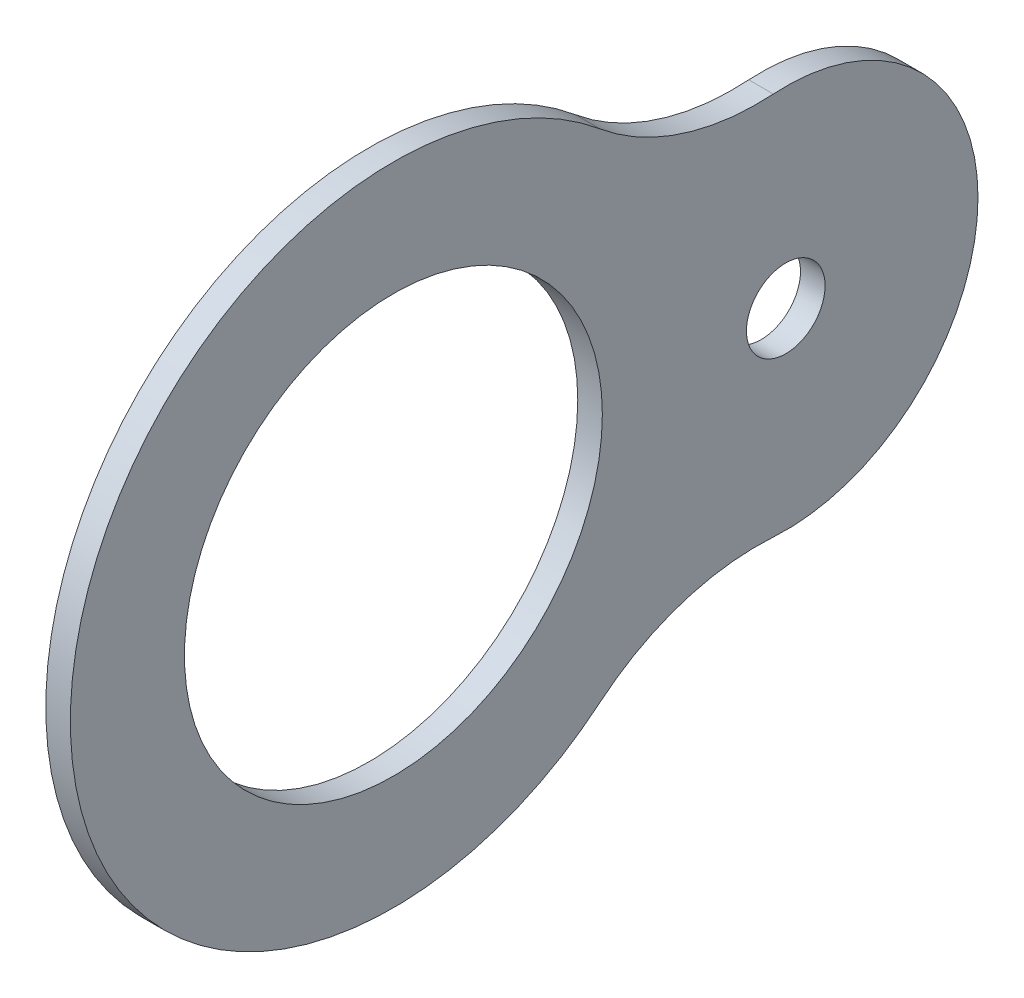
SolidWorks part; units mm, degrees
material "ABS"
ref_plane "Спереди" through (0, 0, 0) normal (0, 0, 1) x (1, 0, 0)
ref_plane "Сверху" through (0, 0, 0) normal (0, 1, 0) x (1, 0, 0)
ref_plane "Справа" through (0, 0, 0) normal (1, 0, 0) x (0, 0, -1)
sketch "Эскиз1" plane through (0, 0, 0) normal (1, 0, 0) x (0, 0, -1)
  circle A0 centre (27.5751, 7.5072) radius 1.5
  circle A1 centre (27.5751, 7.5072) radius 18.465
  circle A2 centre (14.9975, 25.9822) radius 7.885
  circle A3 centre (14.9975, 25.9822) radius 1.5
  circle A4 centre (0, 0) radius 13.14
  circle A5 centre (15.96, 0) radius 7.82
  circle A6 centre (0, 0) radius 8.5
  circle A7 centre (15.96, 0) radius 1.6
  point P6 (15.96, 0)
  point P7 (0, 0)
  dimension "D1" = 3
  dimension "D2" = 36.93
  dimension "D3" = 15.77
  dimension "D5" = 3
  dimension "D10" = 26.28
  dimension "D11" = 15.64
  dimension "D12" = 17
  dimension "D13" = 3.2
  dimension "D4" = 22.35
  dimension "D6" = 15.96
  dimension "D7" = 30
  dimension "D8" = 26
  dimension "D9" = 13.83
extrude "Бобышка-Вытянуть1" add sketch "Эскиз1" along normal blind 1 contours A5 A1 A4 | A1 A5 A4 | A4 A5 A1 | A5 A4 A1 | A1 A5 A4 A7 | A4 A5 A1
fillet "Скругление1" radius 10 2 edges at (0.5, 6.4049, -11.4733) (0.5, -6.4049, -11.4733)
